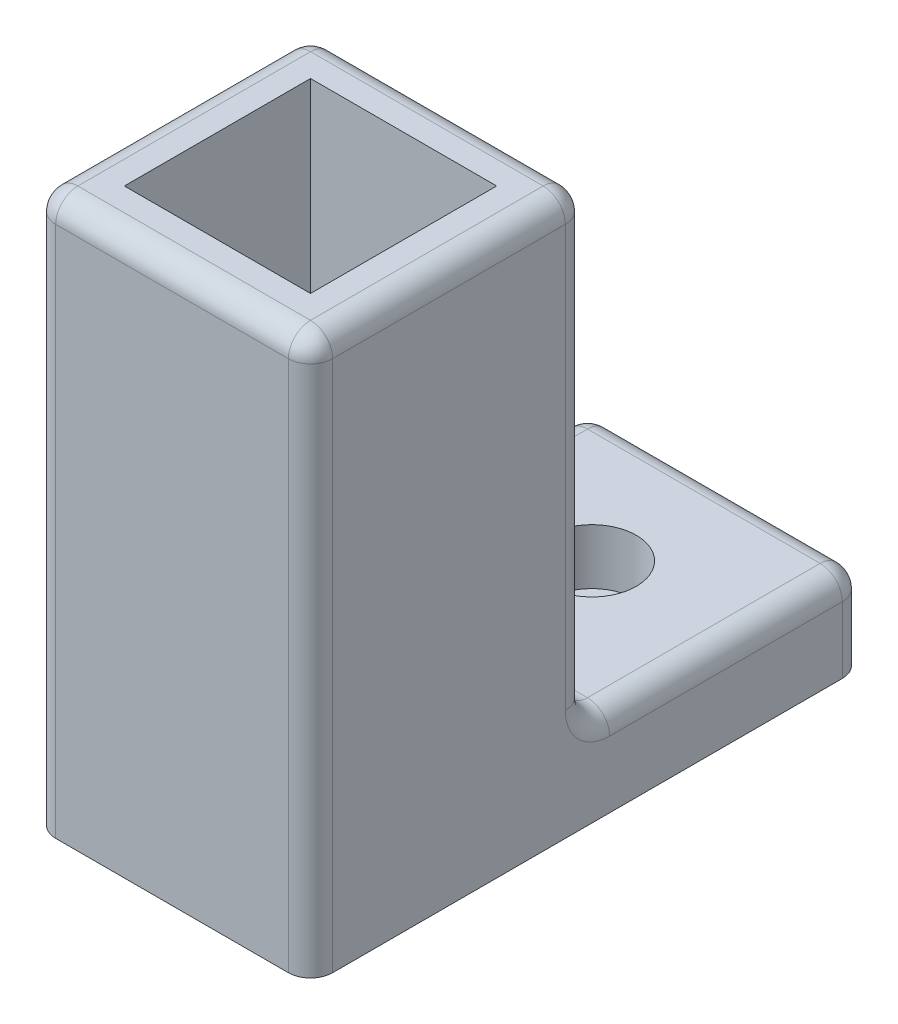
SolidWorks part; units mm, degrees
material "ABS"
ref_plane "Front Plane" through (0, 0, 0) normal (0, 0, 1) x (1, 0, 0)
ref_plane "Top Plane" through (0, 0, 0) normal (0, 1, 0) x (1, 0, 0)
ref_plane "Right Plane" through (0, 0, 0) normal (1, 0, 0) x (0, 0, -1)
sketch "Sketch1" plane through (0, 0, 0) normal (0, 1, 0) x (1, 0, 0)
  line L1 (-8.4, -8.4) -> (8.4, -8.4)
  line L2 (-8.4, -8.4) -> (-8.4, 8.4)
  line L3 (-8.4, 8.4) -> (8.4, 8.4)
  line L4 (8.4, -8.4) -> (8.4, 8.4)
  line L5 (-8.4, -8.4) -> (8.4, 8.4) construction
  line L6 (-8.4, 8.4) -> (8.4, -8.4) construction
  line L7 (-12.5, -12.5) -> (12.5, -12.5)
  line L8 (-12.5, -12.5) -> (-12.5, 12.5)
  line L9 (-12.5, 12.5) -> (12.5, 12.5)
  line L10 (12.5, -12.5) -> (12.5, 12.5)
  line L11 (-12.5, -12.5) -> (12.5, 12.5) construction
  line L12 (-12.5, 12.5) -> (12.5, -12.5) construction
  point P0 (0, 0)
  point P6 (0, 0)
  dimension "D1" = 16.8
  dimension "D2" = 16.8
  dimension "D3" = 25
  dimension "D4" = 25
extrude "Boss-Extrude1" add sketch "Sketch1" along normal blind 50
sketch "Sketch6" plane through (0, 0, 0) normal (0, 1, 0) x (1, 0, 0)
  line L9 (-12.5, -12.5) -> (12.5, -12.5)
  line L10 (-12.5, -12.5) -> (-12.5, 37.5)
  line L11 (-12.5, 37.5) -> (12.5, 37.5)
  line L12 (12.5, -12.5) -> (12.5, 37.5)
  dimension "D1" = 50
  dimension "D2" = 25
  dimension "D3" = 12.5
  dimension "D4" = 12.5
extrude "Boss-Extrude3" add sketch "Sketch6" along normal blind 8
fillet "Fillet2" radius 2 14 edges at (12.5, 4, -37.5) (-12.5, 4, -37.5) (-12.5, 8, -25) (0, 8, -37.5) (12.5, 8, -25) (0, 8, -12.5) (0, 50, -12.5) (12.5, 29, -12.5) (12.5, 50, 0) (12.5, 25, 12.5) (-12.5, 25, 12.5) (0, 50, 12.5) (-12.5, 29, -12.5) (-12.5, 50, 0)
sketch "Sketch7" plane through (0, 8, 0) normal (0, 1, 0) x (1, 0, 0)
  line L0 (0, 0) -> (0, 25.4) construction
  circle A0 centre (0, 0) radius 4
  circle A1 centre (0, 25.4) radius 4
extrude "Cut-Extrude1" cut sketch "Sketch7" against normal blind 5
sketch "Sketch8" plane through (0, 0, 0) normal (0, 1, 0) x (1, 0, 0)
  line L0 (0, 0) -> (0, 25.4) construction
  circle A0 centre (0, 0) radius 2.3813
  circle A1 centre (0, 25.4) radius 2.3813
extrude "Cut-Extrude4" cut sketch "Sketch8" against normal through all and the other way through all
